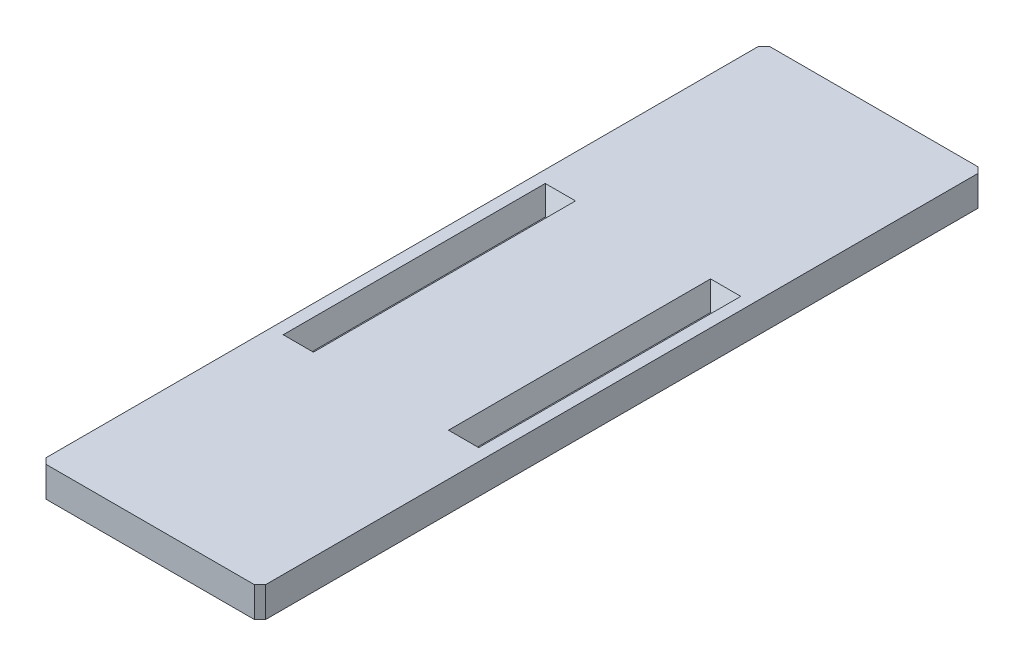
SolidWorks part; units mm, degrees
ref_plane "前视基准面" through (0, 0, 0) normal (0, 0, 1) x (1, 0, 0)
ref_plane "上视基准面" through (0, 0, 0) normal (0, 1, 0) x (1, 0, 0)
ref_plane "右视基准面" through (0, 0, 0) normal (1, 0, 0) x (0, 0, -1)
sketch "草图1" plane through (0, 0, 0) normal (0, 1, 0) x (1, 0, 0)
  line L1 (0, 0) -> (11.3, 0)
  line L2 (0, 0) -> (0, -36.3)
  line L3 (0, -36.3) -> (11.3, -36.3)
  line L4 (11.3, 0) -> (11.3, -36.3)
  dimension "D1" = 36.3
  dimension "D2" = 11.3
extrude "凸台-拉伸1" add sketch "草图1" along normal blind 1.5
chamfer "倒角1" distance 0.4 angle 45 4 edges at (0, 0.75, 36.3) (11.3, 0.75, 36.3) (11.3, 0.75, 0) (0, 0.75, 0)
sketch "草图2" plane through (0, 1.5, 0) normal (0, 1, 0) x (1, 0, 0)
  line L0 (0, -18.15) -> (19.1359, -18.15) construction
  line L1 (0, -0.4) -> (0, -35.9) construction
  line L2 (11.3, -35.9) -> (11.3, -0.4) construction
  line L3 (0.8, -11.65) -> (2.3, -11.65)
  line L4 (0.8, -11.65) -> (0.8, -24.65)
  line L5 (0.8, -24.65) -> (2.3, -24.65)
  line L6 (2.3, -11.65) -> (2.3, -24.65)
  line L7 (10.5, -11.65) -> (9, -11.65)
  line L8 (10.5, -11.65) -> (10.5, -24.65)
  line L9 (10.5, -24.65) -> (9, -24.65)
  line L10 (9, -11.65) -> (9, -24.65)
  dimension "D1" = 13
  dimension "D2" = 13
  dimension "D3" = 1.5
  dimension "D4" = 1.5
  dimension "D5" = 0.8
  dimension "D6" = 0.8
extrude "切除-拉伸1" cut sketch "草图2" against normal blind 1 draft 24
sketch "草图3" plane through (0, 1.5, 0) normal (0, 1, 0) x (1, 0, 0)
  line L0 (0.2, -0.4828) -> (0.2, -35.8172)
  line L1 (0.2, -35.8172) -> (0.4828, -36.1)
  line L2 (0.4828, -36.1) -> (10.8172, -36.1)
  line L3 (10.8172, -36.1) -> (11.1, -35.8172)
  line L4 (11.1, -35.8172) -> (11.1, -0.4828)
  line L5 (11.1, -0.4828) -> (10.8172, -0.2)
  line L6 (10.8172, -0.2) -> (0.4828, -0.2)
  line L7 (0.4828, -0.2) -> (0.2, -0.4828)
  line L8 (0, -0.4) -> (0, -35.9)
  line L9 (0, -35.9) -> (0.4, -36.3)
  line L10 (0.4, -36.3) -> (10.9, -36.3)
  line L11 (10.9, -36.3) -> (11.3, -35.9)
  line L12 (11.3, -35.9) -> (11.3, -0.4)
  line L13 (11.3, -0.4) -> (10.9, 0)
  line L14 (10.9, 0) -> (0.4, 0)
  line L15 (0.4, 0) -> (0, -0.4)
  line L16 (0, -0.4) -> (0, -35.9)
  line L17 (0, -35.9) -> (0.4, -36.3)
  line L18 (0.4, -36.3) -> (10.9, -36.3)
  line L19 (10.9, -36.3) -> (11.3, -35.9)
  line L20 (11.3, -35.9) -> (11.3, -0.4)
  line L21 (11.3, -0.4) -> (10.9, 0)
  line L22 (10.9, 0) -> (0.4, 0)
  line L23 (0.4, 0) -> (0, -0.4)
  dimension "D1" = 0
  dimension "D2" = 0.2
extrude "切除-拉伸2" cut sketch "草图3" against normal blind 10
